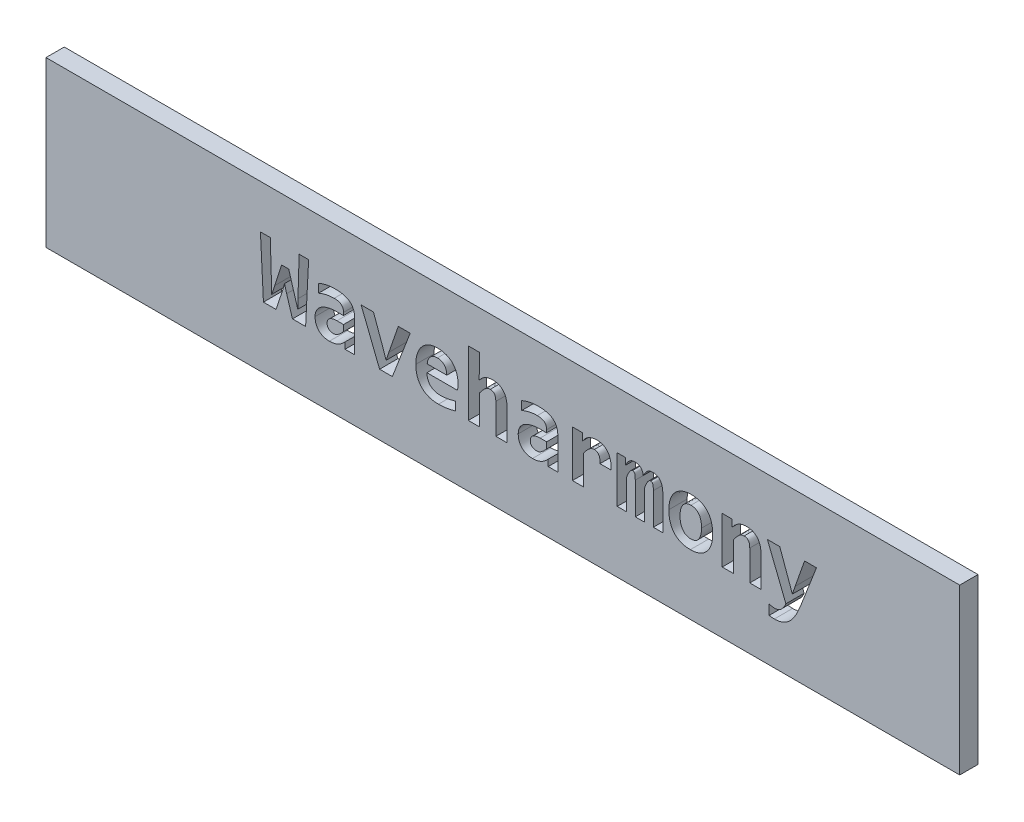
SolidWorks part; units mm, degrees
ref_plane "Front Plane" through (0, 0, 0) normal (0, 0, 1) x (1, 0, 0)
ref_plane "Top Plane" through (0, 0, 0) normal (0, 1, 0) x (1, 0, 0)
ref_plane "Right Plane" through (0, 0, 0) normal (1, 0, 0) x (0, 0, -1)
sketch "Sketch1" plane through (0, 0, 0) normal (0, 0, 1) x (1, 0, 0)
  line L1 (-50, -9) -> (50, -9)
  line L2 (-50, -9) -> (-50, 9)
  line L3 (-50, 9) -> (50, 9)
  line L4 (50, -9) -> (50, 9)
  line L5 (0, 9) -> (0, -9) construction
  line L6 (-50, 0) -> (50, 0) construction
  point P0 (0, 0)
  dimension "D1" = 18
  dimension "D2" = 100
extrude "Boss-Extrude1" add sketch "Sketch1" along normal blind 2
sketch "Sketch2" plane through (0, 0, 2) normal (0, 0, 1) x (1, 0, 0)
  text T0 "<b>Waveharmony</b>" font "Consolas" height 6.5
extrude "Cut-Extrude1" cut sketch "Sketch2" against normal blind 2
